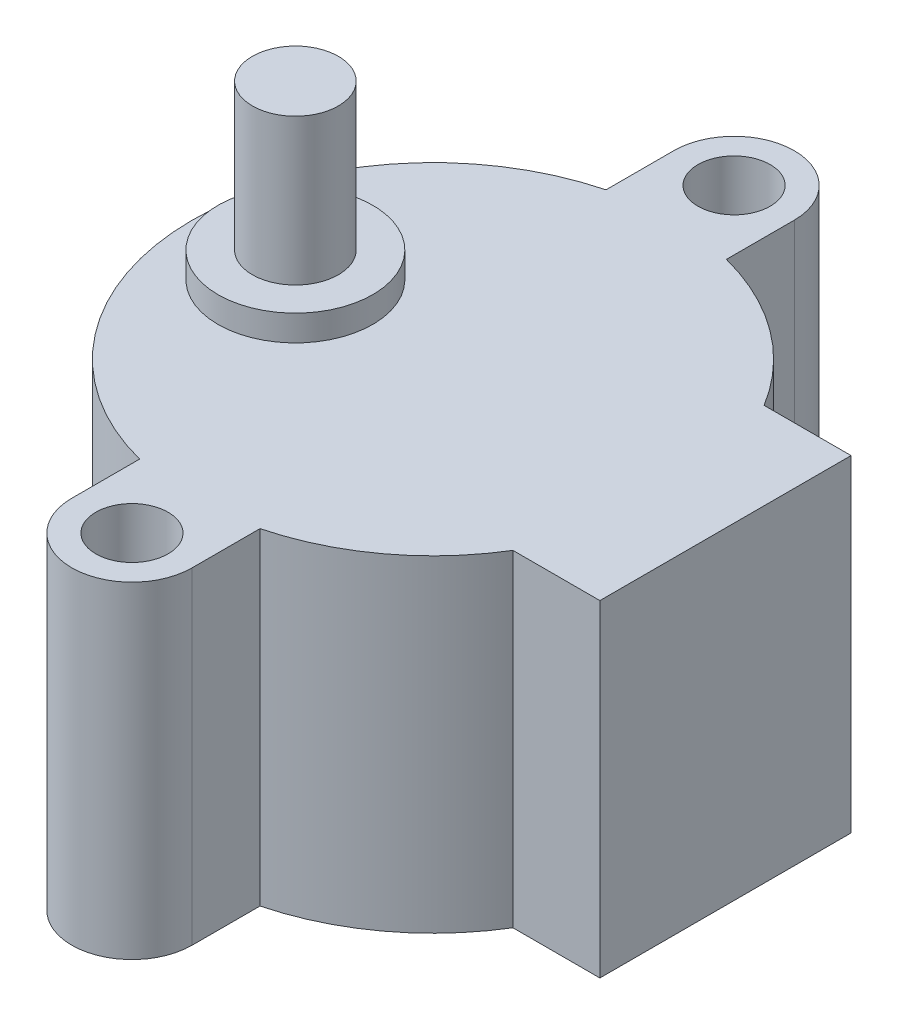
SolidWorks part; units mm, degrees
ref_plane "Front" through (0, 0, 0) normal (0, 0, 1) x (1, 0, 0)
ref_plane "Top" through (0, 0, 0) normal (0, 1, 0) x (1, 0, 0)
ref_plane "Right" through (0, 0, 0) normal (1, 0, 0) x (0, 0, -1)
sketch "Sketch1" plane through (0, 0, 0) normal (0, 1, 0) x (1, 0, 0)
  line L0 (0, -17.5) -> (0, 17.5) construction
  line L1 (-3.5, -17.5) -> (-3.5, 17.5)
  line L2 (3.5, -17.5) -> (3.5, 17.5)
  line L4 (11.9461, 7.3) -> (17, 7.3)
  line L5 (11.9461, 7.3) -> (11.9461, -7.3)
  line L6 (11.9461, -7.3) -> (17, -7.3)
  line L7 (17, 7.3) -> (17, -7.3)
  line L8 (14.4731, -7.3) -> (14.4731, 7.3) construction
  line L9 (11.9461, 0) -> (17, 0) construction
  arc A0 (-3.5, -17.5) -> (3.5, -17.5) centre (0, -17.5) ccw
  arc A1 (3.5, 17.5) -> (-3.5, 17.5) centre (0, 17.5) ccw
  circle A2 centre (0, 0) radius 14
  circle A3 centre (0, -17.5) radius 2.1
  circle A4 centre (0, 17.5) radius 2.1
  point P2 (0, 0)
  point P87 (14.4731, 0)
  dimension "D2" = 3.5
  dimension "D3" = 28
  dimension "D6" = 4.2
  dimension "D1" = 35
  dimension "D4" = 14.6
  dimension "D5" = 17
extrude "Boss-Extrude1" add sketch "Sketch1" against normal blind 19 contours L1 A2 | L2 A2 L1 | A2 L1 A0 L2 | L2 A2 L5 | A2 L2 A1 L1 | A2 L6 L7 L4 | L5 A2
sketch "Sketch2" plane through (0, 0, 0) normal (0, 1, 0) x (1, 0, 0)
  line L0 (-8, 0) -> (0, 0) construction
  circle A0 centre (-8, 0) radius 4.5
  dimension "D2" = 9
  dimension "D1" = 8
extrude "Boss-Extrude2" add sketch "Sketch2" along normal blind 1.5
sketch "Sketch3" plane through (0, 1.5, 0) normal (0, 1, 0) x (1, 0, 0)
  circle A0 centre (-8, 0) radius 2.5
  dimension "D1" = 5
extrude "Boss-Extrude3" add sketch "Sketch3" along normal blind 8.5
